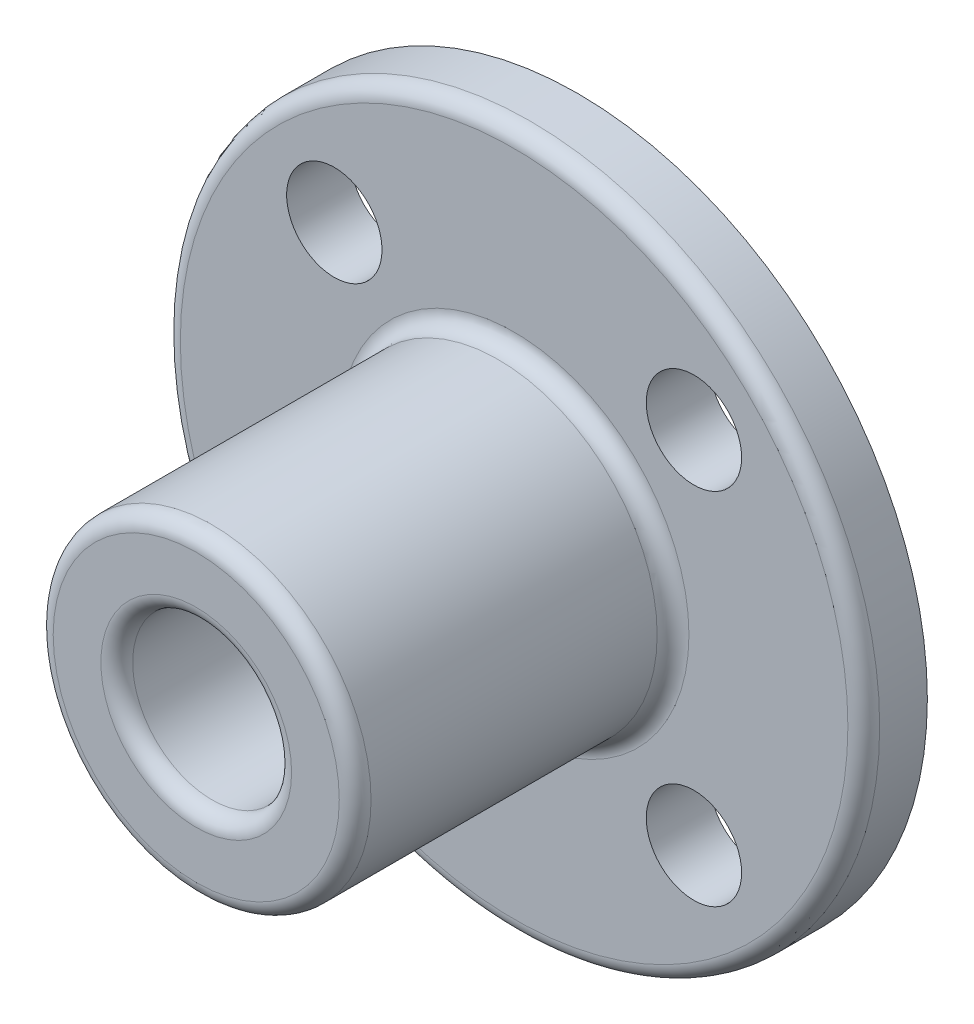
SolidWorks part; units mm, degrees
ref_plane "Front Plane" through (0, 0, 0) normal (0, 0, 1) x (1, 0, 0)
ref_plane "Top Plane" through (0, 0, 0) normal (0, 1, 0) x (1, 0, 0)
ref_plane "Right Plane" through (0, 0, 0) normal (1, 0, 0) x (0, 0, -1)
sketch "Sketch1" plane through (0, 0, 0) normal (0, 0, 1) x (1, 0, 0)
  line L1 (-5.656, 5.6577) -> (5.656, 5.6577) construction
  line L2 (-5.656, 5.6577) -> (-5.656, -5.6577) construction
  line L3 (-5.656, -5.6577) -> (5.656, -5.6577) construction
  line L4 (5.656, 5.6577) -> (5.656, -5.6577) construction
  circle A0 centre (0, 0) radius 11
  circle A1 centre (0, 0) radius 2.5
  circle A2 centre (-5.656, 5.6577) radius 1.5
  circle A3 centre (5.656, 5.6577) radius 1.5
  circle A4 centre (5.656, -5.6577) radius 1.5
  circle A5 centre (-5.656, -5.6577) radius 1.5
  point P12 (0, 0)
  point P15 (0, 0)
  point P16 (0, 5.6577)
  point P17 (5.656, 0)
  dimension "D1" = 22
  dimension "D4" = 5
  dimension "D2" = 3
  dimension "D3" = 16
  dimension "D5" = 11.3154
extrude "Boss-Extrude1" add sketch "Sketch1" along normal blind 2
sketch "Sketch2" plane through (0, 0, 2) normal (0, 0, 1) x (1, 0, 0)
  circle A0 centre (0, 0) radius 5
  circle A1 centre (0, 0) radius 2.5
  dimension "D1" = 10
extrude "Boss-Extrude2" add sketch "Sketch2" along normal blind 10
fillet "Fillet1" radius 0.5 4 edges at (11, 0, 2) (5, 0, 12) (2.5, 0, 12) (5, 0, 2)
